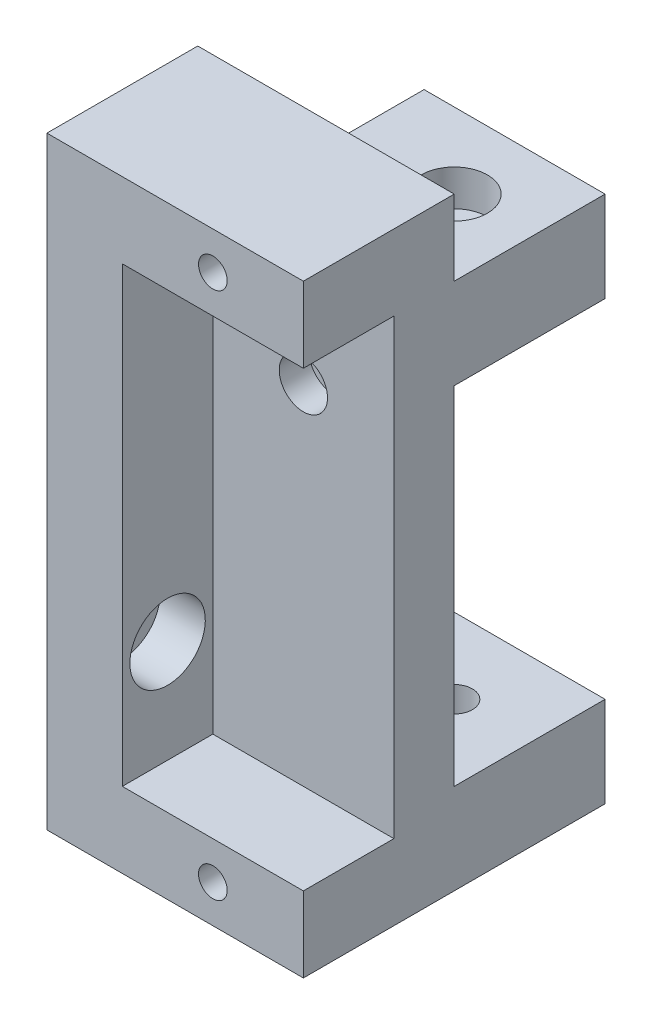
SolidWorks part; units mm, degrees
ref_plane "Plan de face" through (0, 0, 0) normal (0, 0, 1) x (1, 0, 0)
ref_plane "Plan de dessus" through (0, 0, 0) normal (0, 1, 0) x (1, 0, 0)
ref_plane "Plan de droite" through (0, 0, 0) normal (1, 0, 0) x (0, 0, -1)
sketch "Esquisse1" plane through (0, 0, 0) normal (0, 0, 1) x (1, 0, 0)
  line L0 (10, 9.5) -> (10, -9.5) construction
  line L1 (-2, -17.5) -> (10, -17.5)
  line L2 (-2, -17.5) -> (-2, 22.5)
  line L3 (-2, 22.5) -> (10, 22.5)
  line L4 (10, -17.5) -> (10, 22.5)
  line L7 (18, 11.5) -> (0, 11.5) construction
  line L8 (18, -11.5) -> (0, -11.5) construction
  line L9 (0, 11.5) -> (0, -11.5) construction
  dimension "D1" = 11
  dimension "D2" = 6
  dimension "D3" = 2
extrude "Boss.-Extru.1" add sketch "Esquisse1" along normal blind 4
sketch "Esquisse2" plane through (0, 0, 0) normal (0, 0, -1) x (-1, 0, 0)
  line L0 (-10, -17.5) -> (-10, 22.5) construction
  line L1 (2, -17.5) -> (-10, -17.5)
  line L2 (2, -17.5) -> (2, -11.5)
  line L3 (2, -11.5) -> (-10, -11.5)
  line L4 (-10, -17.5) -> (-10, -11.5)
  line L5 (-10, -11.5) -> (0, -11.5) construction
extrude "Boss.-Extru.2" add sketch "Esquisse2" along normal blind 10
mirror "Symétrie1" about plane through (0, 0, 0) normal (0, 1, 0) of "Boss.-Extru.2"
sketch "Esquisse3" plane through (0, 0, 4) normal (0, 0, 1) x (1, 0, 0)
  line L0 (11.55, 12.2) -> (15.55, 12.2) construction
  line L1 (10, 22.5) -> (-2, 22.5) construction
  circle A0 centre (4, 10.6) radius 1.6
  point P5 (4, 22.5)
  dimension "D1" = 3.2
extrude "Enlèv. mat.-Extru.1" cut sketch "Esquisse3" against normal blind 2
sketch "Esquisse4" plane through (0, 0, 4) normal (0, 0, 1) x (1, 0, 0)
  line L0 (10, -17.5) -> (10, 22.5) construction
  line L1 (-2, 22.5) -> (10, 22.5)
  line L2 (-2, 22.5) -> (-2, 17.5)
  line L3 (-2, 17.5) -> (10, 17.5)
  line L4 (10, 22.5) -> (10, 17.5)
  line L10 (0, 0) -> (3.8663, 0) construction
  line L16 (-2, -17.5) -> (10, -17.5)
  line L17 (-2, -17.5) -> (-2, -12.5)
  line L18 (-2, -12.5) -> (10, -12.5)
  line L19 (10, -17.5) -> (10, -12.5)
  dimension "D1" = 5
extrude "Boss.-Extru.3" add sketch "Esquisse4" along normal blind 6
sketch "Esquisse5" plane through (0, 0, 10) normal (0, 0, 1) x (1, 0, 0)
  line L0 (0, 0) -> (2.5887, 0) construction
  line L1 (-2, -12.5) -> (-2, -17.5) construction
  line L2 (-2, -17.5) -> (10, -17.5) construction
  line L3 (-2, 22.5) -> (-2, 17.5) construction
  line L4 (-2, 17.5) -> (10, 17.5) construction
  circle A0 centre (4, -15) radius 0.95
  circle A1 centre (4, 20) radius 0.95
  point P8 (-2, -15)
  point P11 (4, -17.5)
  point P18 (-2, 20)
  point P21 (4, 17.5)
  dimension "D1" = 1.9
extrude "Enlèv. mat.-Extru.2" cut sketch "Esquisse5" against normal blind 5
sketch "Esquisse6" plane through (-2, 0, 0) normal (-1, 0, 0) x (0, 0, 1)
  line L0 (10, -17.5) -> (-10, -17.5) construction
  line L1 (10, 22.5) -> (0, 22.5)
  line L2 (10, 22.5) -> (10, -17.5)
  line L3 (10, -17.5) -> (0, -17.5)
  line L4 (0, 22.5) -> (0, -17.5)
extrude "Boss.-Extru.4" add sketch "Esquisse6" along normal blind 5
sketch "Esquisse7" plane through (-2, 0, 0) normal (1, 0, 0) x (0, 0, -1)
  line L0 (-4, 17.5) -> (-4, -12.5) construction
  line L1 (-10, -12.5) -> (-4, -12.5) construction
  circle A0 centre (-7, -5.7) radius 2.5
  dimension "D3" = 5
  dimension "D1" = 3
  dimension "D2" = 6.8
extrude "Enlèv. mat.-Extru.3" cut sketch "Esquisse7" against normal blind 3
sketch "Esquisse10" plane through (0, -17.5, 0) normal (0, -1, 0) x (-1, 0, 0)
  line L0 (-10, 10) -> (2, 10) construction
  line L1 (-10, -10) -> (-10, 10) construction
  point P0 (-5, 5)
  dimension "D1" = 5
  dimension "D2" = 5
hole_wizard "Chambrage pour vis à six pans creux M21" positions "Esquisse10" profile "Esquisse9" counterbore size "M2" standard "ISO"
sketch "Esquisse9" plane through (5, -17.5, -5) normal (1, 0, 0) x (0, 0, -1)
  line L0 (0, 0) -> (0, 6)
  line L1 (0, 6) -> (1.2, 6)
  line L3 (1.2, 6) -> (1.2, 2.4)
  line L4 (1.2, 2.4) -> (2.2, 2.4)
  line L5 (2.2, 2.4) -> (2.2, 0)
  line L7 (2.2, 0) -> (0, 0)
  line L11 (0, -6.35) -> (0, 107.95) construction
  dimension "Diamètre du perçage jusqu'au prochain" = 2.4
  dimension "Profondeur du perçage jusqu'au prochain" = 6
  dimension "Diamètre du chambrage" = 4.4
  dimension "Profondeur du chambrage" = 2.4
mirror "Symétrie2" about plane through (0, 0, 0) normal (0, 1, 0) of "Chambrage pour vis à six pans creux M21"
